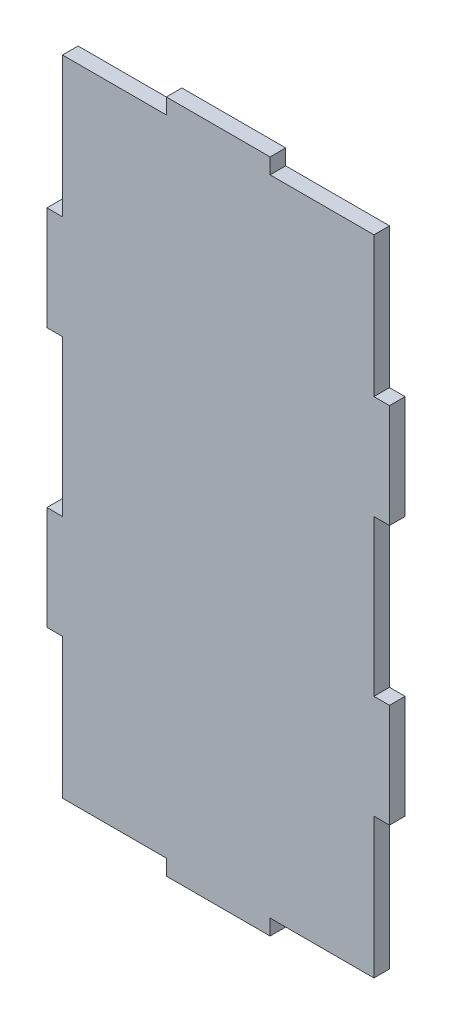
SolidWorks part; units mm, degrees
material "ABS"
ref_plane "Plan de face" through (0, 0, 0) normal (0, 0, 1) x (1, 0, 0)
ref_plane "Plan de dessus" through (0, 0, 0) normal (0, 1, 0) x (1, 0, 0)
ref_plane "Plan de droite" through (0, 0, 0) normal (1, 0, 0) x (0, 0, -1)
sketch "Esquisse1" plane through (0, 0, 0) normal (0, 0, 1) x (1, 0, 0)
  line L0 (30, 25) -> (-30, 25) construction
  line L1 (30, -62) -> (-30, -62)
  line L2 (30, -62) -> (30, 62)
  line L3 (30, 62) -> (-30, 62)
  line L4 (-30, -62) -> (-30, 62)
  line L5 (30, -62) -> (-30, 62) construction
  line L6 (30, 62) -> (-30, -62) construction
  line L7 (30, -25) -> (-30, -25) construction
  line L9 (-27, 15) -> (-33, 15)
  line L10 (-27, 15) -> (-27, 35)
  line L11 (-27, 35) -> (-33, 35)
  line L12 (-33, 15) -> (-33, 35)
  line L13 (-27, 15) -> (-33, 35) construction
  line L14 (-27, 35) -> (-33, 15) construction
  line L15 (10, 59) -> (-10, 59)
  line L16 (10, 59) -> (10, 65)
  line L17 (10, 65) -> (-10, 65)
  line L18 (-10, 59) -> (-10, 65)
  line L19 (10, 59) -> (-10, 65) construction
  line L20 (10, 65) -> (-10, 59) construction
  line L21 (10, -65) -> (-10, -65)
  line L22 (10, -65) -> (10, -59)
  line L23 (10, -59) -> (-10, -59)
  line L24 (-10, -65) -> (-10, -59)
  line L25 (10, -65) -> (-10, -59) construction
  line L26 (10, -59) -> (-10, -65) construction
  line L27 (-27, -35) -> (-33, -35)
  line L28 (-27, -35) -> (-27, -15)
  line L29 (-27, -15) -> (-33, -15)
  line L30 (-33, -35) -> (-33, -15)
  line L31 (-27, -35) -> (-33, -15) construction
  line L32 (-27, -15) -> (-33, -35) construction
  line L33 (33, -35) -> (27, -35)
  line L34 (33, -35) -> (33, -15)
  line L35 (33, -15) -> (27, -15)
  line L36 (27, -35) -> (27, -15)
  line L37 (33, -35) -> (27, -15) construction
  line L38 (33, -15) -> (27, -35) construction
  line L39 (33, 15) -> (27, 15)
  line L40 (33, 15) -> (33, 35)
  line L41 (33, 35) -> (27, 35)
  line L42 (27, 15) -> (27, 35)
  line L43 (33, 15) -> (27, 35) construction
  line L44 (33, 35) -> (27, 15) construction
  point P0 (0, 0)
  point P14 (0, 62)
  point P19 (0, -62)
  dimension "D1" = 60
  dimension "D2" = 124
  dimension "D3" = 50
  dimension "D4" = 25
  dimension "D5" = 6
  dimension "D6" = 20
  dimension "D7" = 20
extrude "Boss.-Extru.1" add sketch "Esquisse1" along normal blind 3 contours L39 L42 L41 L2 L3 L16 L15 L18 L4 L11 L10 L9 L29 L28 L27 L1 L24 L23 L22 L33 L36 L35 | L18 L15 L16 L3 | L18 L3 L16 L17 | L10 L11 L4 L9 | L12 L9 L4 L11 | L40 L41 L2 L39 | L42 L39 L2 L41 | L34 L35 L2 L33 | L36 L33 L2 L35 | L24 L1 L22 L23 | L24 L21 L22 L1 | L28 L29 L4 L27 | L30 L27 L4 L29
